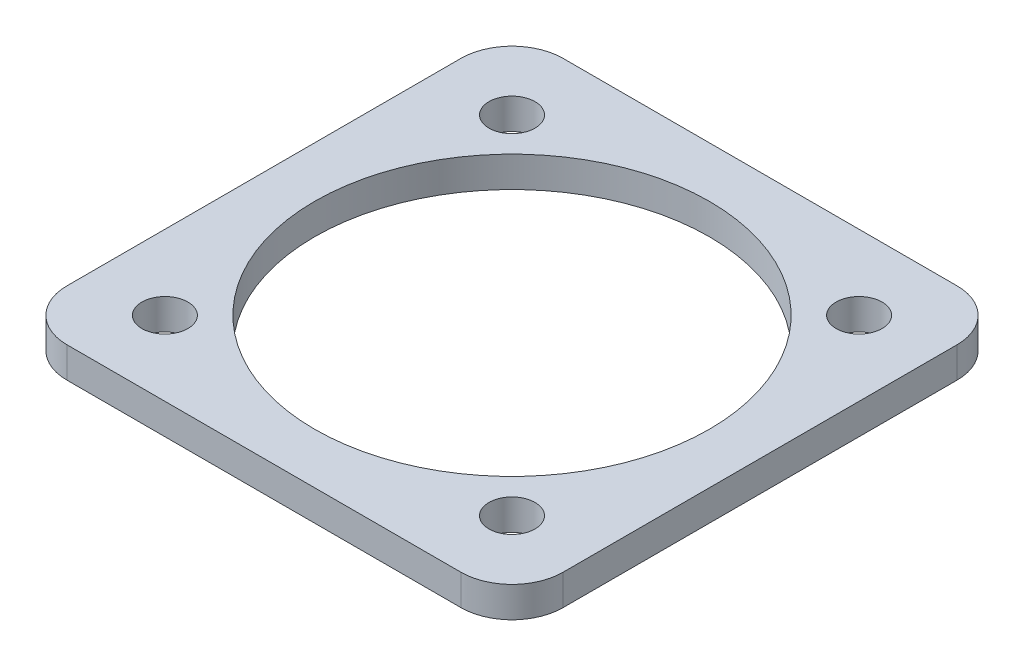
SolidWorks part; units mm, degrees
ref_plane "前视基准面" through (0, 0, 0) normal (0, 0, 1) x (1, 0, 0)
ref_plane "上视基准面" through (0, 0, 0) normal (0, 1, 0) x (1, 0, 0)
ref_plane "右视基准面" through (0, 0, 0) normal (1, 0, 0) x (0, 0, -1)
sketch "草图1" plane through (0, 0, 0) normal (0, 1, 0) x (1, 0, 0)
  line L1 (-19.2538, -24.2538) -> (19.2538, -24.2538)
  line L2 (-24.2538, -19.2538) -> (-24.2538, 19.2538)
  line L3 (-19.2538, 24.2538) -> (19.2538, 24.2538)
  line L4 (24.2538, -19.2538) -> (24.2538, 19.2538)
  line L5 (-24.2538, -24.2538) -> (24.2538, 24.2538) construction
  line L6 (-24.2538, 24.2538) -> (24.2538, -24.2538) construction
  circle A0 centre (0, 0) radius 19.3
  circle A1 centre (0, 0) radius 34.3 construction
  circle A2 centre (-16.9706, 16.9706) radius 2.25
  circle A3 centre (16.9706, 16.9706) radius 2.25
  circle A4 centre (16.9706, -16.9706) radius 2.25
  circle A5 centre (-16.9706, -16.9706) radius 2.25
  arc A6 (-19.2538, -24.2538) -> (-24.2538, -19.2538) centre (-19.2538, -19.2538) cw
  arc A7 (19.2538, -24.2538) -> (24.2538, -19.2538) centre (19.2538, -19.2538) ccw
  arc A8 (19.2538, 24.2538) -> (24.2538, 19.2538) centre (19.2538, 19.2538) cw
  arc A9 (-24.2538, 19.2538) -> (-19.2538, 24.2538) centre (-19.2538, 19.2538) cw
  point P19 (0, 0)
  dimension "D1" = 38.6
  dimension "D3" = 4.5
  dimension "D6" = 5
  dimension "D2" = 15
  dimension "D4" = 24
  dimension "D5" = 4
extrude "凸台-拉伸1" add sketch "草图1" along normal blind 3
equation "\"axis1­_inner_dim\"= 72"
equation "\"axis1_outer_dim\"= 120"
equation "\"axis1_install_inner_dim\" = \"axis1_cross_roller_bear_inner_dim\""
equation "\"axis1_install_outer_dim\" = 60"
equation "\"axis1_install_shell_thick\" = \"shell_thickness_c\""
equation "\"axis1_total_len\"= 170"
equation "\"axis1to2_vertical_dim\"= 30"
equation "\"axis1_cross_roller_bear_inner_dim\" = 52"
equation "\"axis2_inner_dim\"= 40"
equation "\"axis2_outer_dim\"= 90"
equation "\"axis2_install_inner_dim\" = \"vexta_asm46aa2_install_ring_dim\""
equation "\"axis2_install_outer_dim\" = 60"
equation "\"axis2_install_shell_thick\" = \"shell_thickness_c\""
equation "\"axis2_total_len\"= 195"
equation "\"axis2_cam_tangent_weight\"= \"cam_tangent_weight\""
equation "\"axis2_inner_cam_base_rad\"= 50"
equation "\"axis2_inner_cam_lobe_dim\"= 74"
equation "\"axis2_outer_cam_base_rad\"= 45"
equation "\"axis2_outer_cam_lobe_dim\"= 69"
equation "\"axis2_side_cover_cam_base_rad\"= 47.5"
equation "\"axis2_side_cover_cam_lobe_dim\"= 71.5"
equation "\"axis2_side_cover_outer_circle_rad\"= 36"
equation "\"axis2_side_cover_inner_circle_rad\"= 32"
equation "\"axis2_side_cover_small_circle_rad\"= 27"
equation "\"axis2to7_vertical_dim\"= \"axis1to2_vertical_dim\""
equation "\"axis7_inner_dim\"= 40"
equation "\"axis7_outer_dim\"= 94"
equation "\"axis7_install_inner_dim\" = \"vexta_asm46aa2_install_ring_dim\""
equation "\"axis7_install_outer_dim\" = 60"
equation "\"axis7_install_shell_thick\" = \"shell_thickness_c\""
equation "\"axis7_total_len\"= 255"
equation "\"axis7to3_vertical_dim\"= 40.5"
equation "\"axis3_inner_dim\"= 30"
equation "\"axis3_outer_dim\"= 72"
equation "\"axis3_install_inner_dim\" = \"vexta_asm46aa2_install_ring_dim\""
equation "\"axis3_install_outer_dim\" = 60"
equation "\"axis3_install_shell_thick\" = \"shell_thickness_c\""
equation "\"axis3_total_len\"= 195"
equation "\"axis3_cam_tangent_weight\"= \"cam_tangent_weight\""
equation "\"axis3_inner_cam_base_rad\"= 50"
equation "\"axis3_inner_cam_lobe_dim\"= 69"
equation "\"axis3_outer_cam_base_rad\"= 47.5"
equation "\"axis3_outer_cam_lobe_dim\"= 66.5"
equation "\"axis3_side_cover_cam_base_rad\"= 45"
equation "\"axis3_side_cover_cam_lobe_dim\"= 64"
equation "\"axis3_side_cover_outer_circle_rad\"= 25"
equation "\"axis3_side_cover_inner_circle_rad\"= 17.5"
equation "\"axis3_side_cover_small_circle_rad\"= 13"
equation "\"axis3to4_vertical_dim\"= \"axis7to3_vertical_dim\""
equation "\"axis4_inner_dim\"= 30"
equation "\"axis4_outer_dim\"= 75"
equation "\"axis4_install_inner_dim\" = \"vexta_arm24sak_install_ring_dim\" "
equation "\"axis4_install_outer_dim\" = 60"
equation "\"axis4_install_shell_thick\" = \"shell_thickness_c\""
equation "\"axis4_total_len\"= 265"
equation "\"axis4to5_vertical_dim\"= 27"
equation "\"axis5_inner_dim\"= 30"
equation "\"axis5_outer_dim\"= 50"
equation "\"axis5_install_inner_dim\" = \"vexta_arm24sak_install_ring_dim\""
equation "\"axis5_install_outer_dim\" = 60"
equation "\"axis5_install_shell_thick\" = \"shell_thickness_c\""
equation "\"axis5_total_len\"=160"
equation "\"axis5_cam_tangent_weight\"= \"cam_tangent_weight\""
equation "\"axis5_inner_cam_base_rad\"= 34"
equation "\"axis5_inner_cam_lobe_dim\"= 54"
equation "\"axis5_outer_cam_base_rad\"= 31"
equation "\"axis5_outer_cam_lobe_dim\"= 51"
equation "\"axis5_side_cover_cam_base_rad\"= 30"
equation "\"axis5_side_cover_cam_lobe_dim\"= 50"
equation "\"axis5_side_cover_outer_circle_rad\"= 22"
equation "\"axis5_side_cover_inner_circle_rad\"= 14"
equation "\"axis5_side_cover_small_circle_rad\"= 11"
equation "\"axis5to6_vertical_dim\"= \"axis4to5_vertical_dim\""
equation "\"axis6_inner_dim\"= 20"
equation "\"axis6_outer_dim\"= 48.5"
equation "\"axis6_install_inner_dim\" = \"vexta_arm24sak_install_ring_dim\""
equation "\"axis6_install_outer_dim\" = 60"
equation "\"axis6_install_shell_thick\" = \"shell_thickness_c\""
equation "\"axis6_total_len\"= 36"
equation "\"cam_tangent_weight\"= 5"
equation "\"trapezoidal_circle_tangent_weight_center\"= 10"
equation "\"trapezoidal_circle_tangent_weight_edge\"= 10"
equation "\"shell_thickness_a\"= 2"
equation "\"shell_thickness_b\"= 4"
equation "\"shell_thickness_c\" = 6"
equation "\"inner_shell_thick\"= 2"
equation "\"outer_shell_thick\"= 4"
equation "\"shell_thick_adjust\"= 0"
equation "\"fit_tolerance_adjust_a\"= 0.2"
equation "\"fit_tolerance_adjust_b\"= 0.1"
equation "\"fit_tolerance_adjust_c\" = 0.5"
equation "\"m2.5_screw_hole_depth\"= 10"
equation "\"m2.5_screw_through_hole_outer_depth\"= 2"
equation "\"m2.5_screw_through_hole_inner_dim\"= 2.9"
equation "\"m2.5_screw_through_hole_outer_dim\"= 5.5"
equation "\"m2.5_screw_self_tapping_hole_dim\"= 2.1"
equation "\"m3_screw_hole_depth\"= 10"
equation "\"m3_screw_through_hole_outer_depth\"= 3"
equation "\"m3_screw_through_hole_inner_dim\"= 3.4"
equation "\"m3_screw_through_hole_outer_dim\"= 6"
equation "\"m3_screw_self_tapping_hole_dim\"= 2.5"
equation "\"m3_screw_self_tapping_hole_depth\" = 10"
equation "\"m4_screw_hole_depth\"= 10"
equation "\"m4_screw_through_hole_outer_depth\"= 4.5"
equation "\"m4_screw_through_hole_inner_dim\"= 4.5"
equation "\"m4_screw_through_hole_outer_dim\"= 7.5"
equation "\"m4_screw_self_tapping_hole_dim\"= 3.5"
equation "\"m4_screw_self_tapping_hole_depth\" = 10"
equation "\"vexta_asm46aa2_install_ring_dim\"= 37.6"
equation "\"vexta_asm46aa2_install_ring_thickness\" = 2"
equation "\"vexta_asm46aa2_install_base_m4_screw_depth\"= 9"
equation "\"vexta_asm46aa2_install_ring_m3_screw_depth\" = 6"
equation "\"vexta_asm46aa2_h_gear_install_dim\"= 20.5"
equation "\"vexta_asm46aa2_h_gear_install_m3_screw_depth\"= 5"
equation "\"vexta_asm46aa2_axis_dim\"= 10"
equation "\"vexta_arm24sak_install_ring_dim\"= 29"
equation "\"vexta_arm24sak_install_ring_thickness\" = 2.5"
equation "\"vexta_arm24sak_install_base_m3_screw_depth\"= 7"
equation "\"vexta_arm24sak_install_ring_m3_screw_depth\" = 4.5"
equation "\"vexta_arm24sak_h_gear_install_dim\"= 15.5"
equation "\"vexta_arm24sak_h_gear_install_m3_screw_depth\"= 5"
equation "\"vexta_arm24sak_axis_dim\"= 8"
equation "\"enabot_v3_scale_factor\"= 1.2"
equation "\"D1@草图1\"=(\"vexta_asm46aa2_install_ring_dim\" + \"fit_tolerance_adjust_c\" * 2)"
